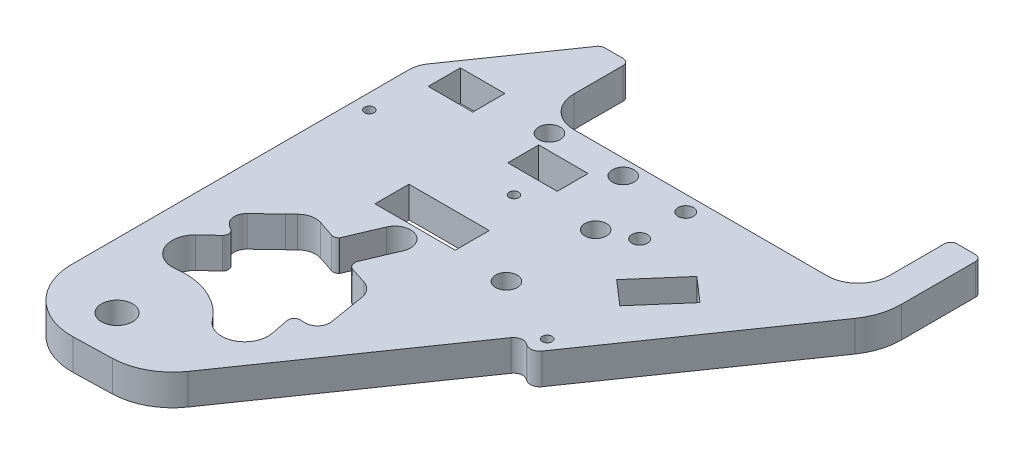
SolidWorks part; units mm, degrees
ref_plane "Płaszczyzna przednia" through (0, 0, 0) normal (0, 0, 1) x (1, 0, 0)
ref_plane "Płaszczyzna górna" through (0, 0, 0) normal (0, 1, 0) x (1, 0, 0)
ref_plane "Płaszczyzna prawa" through (0, 0, 0) normal (1, 0, 0) x (0, 0, -1)
sketch "Szkic2" plane through (0, 0, 0) normal (0, 1, 0) x (1, 0, 0)
  line L0 (-2.7059, 127.916) -> (-8.7059, 127.916)
  line L1 (-32.7793, 94.7431) -> (-10.3657, 127.0559) construction
  line L3 (103.2941, 130) -> (109.2941, 130)
  line L4 (-32.7793, 94.7431) -> (-10.3657, 127.0559)
  line L5 (-34.2059, 90.1835) -> (-34.2059, -19.1544) construction
  line L6 (-8.7059, 127.916) -> (-8.7223, 127.916)
  line L7 (111.2941, 128) -> (111.2941, 118.285)
  line L9 (-34.2059, 90.1835) -> (-34.2059, -19.1544)
  line L10 (55.0272, 21.5459) -> (-2.7136, -35.9345)
  line L11 (-0.7059, 110) -> (-0.7059, 125.916) construction
  line L12 (-13.6937, -39.1478) -> (-2.7136, -35.9345)
  line L13 (9.2941, 100) -> (91.2941, 100)
  line L14 (-0.7059, 110) -> (-0.7059, 125.916)
  line L15 (85.9359, 90.0901) -> (91.3711, 90.0901)
  line L18 (56.7941, 25.7981) -> (56.7941, 59.3339)
  line L20 (101.2941, 110) -> (101.2941, 118.285)
  line L21 (111.2941, 110.0131) -> (111.2941, 118.285)
  line L28 (101.2941, 128) -> (101.2941, 118.285)
  arc A0 (-8.7223, 127.916) -> (-10.3657, 127.0559) centre (-8.7223, 125.916) ccw construction
  arc A1 (101.2941, 110) -> (91.2941, 100) centre (91.2941, 110) cw
  arc A3 (-34.2059, -19.1544) -> (-13.6937, -39.1478) centre (-14.2059, -19.1544) ccw construction
  arc A5 (-32.7793, 94.7431) -> (-34.2059, 90.1835) centre (-26.2059, 90.1835) ccw construction
  arc A6 (91.3711, 90.0901) -> (111.2941, 110.0131) centre (91.3711, 110.0131) ccw
  arc A7 (-34.2059, -19.1544) -> (-13.6937, -39.1478) centre (-14.2059, -19.1544) ccw
  arc A8 (-8.7223, 127.916) -> (-10.3657, 127.0559) centre (-8.7223, 125.916) ccw
  arc A9 (-32.7793, 94.7431) -> (-34.2059, 90.1835) centre (-26.2059, 90.1835) ccw
  arc A10 (-0.7059, 125.916) -> (-2.7059, 127.916) centre (-2.7059, 125.916) ccw construction
  arc A11 (-0.7059, 110) -> (9.2941, 100) centre (9.2941, 110) ccw construction
  arc A12 (-0.7059, 125.916) -> (-2.7059, 127.916) centre (-2.7059, 125.916) ccw
  arc A13 (-0.7059, 110) -> (9.2941, 100) centre (9.2941, 110) ccw
  arc A15 (109.2941, 130) -> (111.2941, 128) centre (109.2941, 128) cw
  arc A16 (101.2941, 128) -> (103.2941, 130) centre (103.2941, 128) cw
  arc A20 (55.0272, 21.5459) -> (56.7941, 25.7981) centre (50.7941, 25.7981) ccw
  arc A21 (85.9359, 90.0901) -> (56.7941, 59.3339) centre (85.7027, 61.1269) ccw
  point P0 (-0.0663, -32.3728)
  point P1 (26.0174, 75.6612)
  point P7 (22.4343, 73.3976)
  point P10 (-27.8527, -17.9733)
  point P17 (-26.5261, -18.235)
  point P19 (48.8941, 59.2598)
  dimension "D8" = 2
  dimension "D2" = 10
  dimension "D3" = 10
extrude "Dodanie-wyciągnięcie1" add sketch "Szkic2" along normal blind 10 separate body
sketch "Szkic5" plane through (0, 10, 0) normal (0, 1, 0) x (1, 0, 0)
  circle A0 centre (-13.2962, -25.3039) radius 5.05
  dimension "D6" = 10.1
  dimension "D2" = 0
extrude "Wytnij-wyciągnięcie1" cut sketch "Szkic5" against normal blind 10
sketch "Szkic9" plane through (0, 10, 0) normal (0, 1, 0) x (1, 0, 0)
  line L0 (-2.1059, 47) -> (23.8941, 47) construction
  line L1 (23.8941, 47) -> (23.8941, 58) construction
  line L2 (-2.1059, 58) -> (-2.1059, 47) construction
  line L3 (23.8941, 58) -> (-2.1059, 58) construction
  line L4 (7.8941, 90) -> (7.8941, 80) construction
  line L5 (23.8941, 90) -> (7.8941, 90) construction
  line L6 (23.8941, 80) -> (23.8941, 90) construction
  line L7 (7.8941, 80) -> (23.8941, 80) construction
  line L8 (-2.1059, 47) -> (23.8941, 47)
  line L9 (23.8941, 47) -> (23.8941, 58)
  line L10 (-2.1059, 58) -> (-2.1059, 47)
  line L11 (23.8941, 58) -> (-2.1059, 58)
  line L12 (7.8941, 90) -> (7.8941, 80)
  line L13 (23.8941, 90) -> (7.8941, 90)
  line L14 (23.8941, 80) -> (23.8941, 90)
  line L15 (7.8941, 80) -> (23.8941, 80)
  circle A13 centre (17.8941, 72) radius 1.55 construction
  circle A14 centre (17.8941, 72) radius 1.55
extrude "Wytnij-wyciągnięcie3" cut sketch "Szkic9" against normal through all
sketch "Szkic12" plane through (0, 10, 0) normal (0, 1, 0) x (1, 0, 0)
  circle A0 centre (40.8941, 46.55) radius 1.55 construction
  circle A1 centre (30.2605, 95) radius 1.55 construction
  circle A2 centre (6.3605, 95) radius 1.55 construction
  circle A3 centre (40.8941, 46.55) radius 1.55
  circle A4 centre (30.2605, 95) radius 1.55
  circle A5 centre (6.3605, 95) radius 1.55
  circle A6 centre (40.8941, 75.45) radius 1.55 construction
  circle A7 centre (40.8941, 75.45) radius 1.55
  circle A8 centre (40.8941, 46.55) radius 3.5
  circle A9 centre (30.2605, 95) radius 3.5
  circle A10 centre (6.3605, 95) radius 3.5
  circle A11 centre (40.8941, 75.45) radius 3.5
  dimension "D1" = 7
  dimension "D2" = 7
  dimension "D3" = 7
  dimension "D4" = 7
sketch "Szkic13" plane through (0, 10, 0) normal (0, 1, 0) x (1, 0, 0)
  circle A0 centre (40.8941, 75.45) radius 3.5 construction
  circle A1 centre (40.8941, 46.55) radius 3.5 construction
  circle A2 centre (30.2605, 95) radius 3.5 construction
  circle A3 centre (6.3605, 95) radius 3.5 construction
  circle A4 centre (40.8941, 75.45) radius 3.5
  circle A5 centre (40.8941, 46.55) radius 3.5
  circle A6 centre (30.2605, 95) radius 3.5
  circle A7 centre (6.3605, 95) radius 3.5
extrude "Wytnij-wyciągnięcie5" cut sketch "Szkic13" against normal through all
sketch "Szkic16" plane through (0, 10, 0) normal (0, 1, 0) x (1, 0, 0)
  line L4 (78.2039, 71.9086) -> (70.359, 78.7363)
  line L5 (70.359, 78.7363) -> (58.2793, 64.8568)
  line L6 (58.2793, 64.8568) -> (66.1242, 58.0291)
  line L7 (66.1242, 58.0291) -> (78.2039, 71.9086)
  line L12 (70.3785, 78.4541) -> (58.5614, 64.8763)
  line L13 (58.5614, 64.8763) -> (66.1047, 58.3113)
  line L14 (66.1047, 58.3113) -> (77.9217, 71.8891)
  line L15 (77.9217, 71.8891) -> (70.3785, 78.4541)
  line L16 (70.3785, 78.4541) -> (58.5614, 64.8763)
  line L17 (58.5614, 64.8763) -> (66.1047, 58.3113)
  line L18 (66.1047, 58.3113) -> (77.9217, 71.8891)
  line L19 (77.9217, 71.8891) -> (70.3785, 78.4541)
  dimension "D1" = 0
  dimension "D2" = 0.2
sketch "Szkic18" plane through (0, 10, 0) normal (0, 1, 0) x (1, 0, 0)
  line L0 (-26.2059, 88.7461) -> (-26.2059, 98.7461) construction
  line L1 (-12.2059, 88.7461) -> (-12.2059, 98.7461) construction
  line L3 (-14.2059, 98.7461) -> (-24.2059, 98.7461) construction
  line L4 (-12.0059, 98.9461) -> (-26.4059, 98.9461)
  line L5 (-26.4059, 98.9461) -> (-26.4059, 88.5461)
  line L6 (-26.4059, 88.5461) -> (-12.0059, 88.5461)
  line L7 (-12.0059, 88.5461) -> (-12.0059, 98.9461)
  line L12 (-14.2059, 88.7461) -> (-24.2059, 88.7461) construction
  line L15 (-26.2059, 98.7461) -> (-26.2059, 88.7461)
  line L16 (-12.2059, 98.7461) -> (-26.2059, 98.7461)
  line L18 (-26.2059, 88.7461) -> (-12.2059, 88.7461)
  line L19 (-12.2059, 88.7461) -> (-12.2059, 98.7461)
  line L20 (-26.2059, 98.7461) -> (-26.2059, 88.7461) construction
  line L21 (-12.2059, 88.7461) -> (-12.2059, 98.7461) construction
  dimension "D3" = 0
  dimension "D1" = 0
  dimension "D4" = 0
  dimension "D5" = 0
  dimension "D2" = 0.2
sketch "Szkic19" plane through (0, 10, 0) normal (0, 1, 0) x (1, 0, 0)
  line L4 (-26.4059, 88.5461) -> (-12.0059, 88.5461) construction
  line L5 (-12.0059, 88.5461) -> (-12.0059, 98.9461) construction
  line L6 (-12.0059, 98.9461) -> (-26.4059, 98.9461) construction
  line L7 (-26.4059, 98.9461) -> (-26.4059, 88.5461) construction
  line L8 (-26.4059, 88.5461) -> (-12.0059, 88.5461)
  line L9 (-12.0059, 88.5461) -> (-12.0059, 98.9461)
  line L10 (-12.0059, 98.9461) -> (-26.4059, 98.9461)
  line L11 (-26.4059, 98.9461) -> (-26.4059, 88.5461)
extrude "Wytnij-wyciągnięcie7" cut sketch "Szkic19" against normal through all
sketch "Szkic20" plane through (0, 0, 0) normal (0, -1, 0) x (1, 0, 0)
  circle A0 centre (-29.3372, -72.3879) radius 1.55 construction
  circle A1 centre (-29.3372, -72.3879) radius 1.55
extrude "Wytnij-wyciągnięcie8" cut sketch "Szkic20" against normal blind 10
sketch "Szkic23" plane through (0, 10, 0) normal (0, 1, 0) x (1, 0, 0)
  line L0 (15.6287, 38.3507) -> (8.5974, 21.8895)
  line L1 (8.5974, 21.8895) -> (-0.7827, 25.8961)
  line L2 (-0.7827, 25.8961) -> (6.2486, 42.3573)
  line L4 (-2.7136, -35.9345) -> (55.0272, 21.5459) construction
  circle A0 centre (-13.2962, -25.3039) radius 5.05 construction
  arc A1 (15.6287, 38.3507) -> (6.2486, 42.3573) centre (10.9387, 40.354) ccw
  dimension "D8" = 10.2
  dimension "D1" = 10.2
  dimension "D2" = 17.9
  dimension "D3" = 22
  dimension "D4" = 33
  dimension "D5" = 52
  dimension "D6" = 5.1
extrude "Wytnij-wyciągnięcie10" cut sketch "Szkic23" against normal blind 10
ref_plane "Płaszczyzna1" through (-7.7499, 0, -13.8978) normal (-0.5026, 0, 0.8645) x (0.8645, 0, 0.5026)
sketch "Szkic25" plane through (0, 10, 0) normal (0, 1, 0) x (1, 0, 0)
  line L0 (1.6794, 31.6602) -> (3.4697, 35.8516)
  line L1 (-22.4924, 9.2261) -> (1.6794, 31.6602)
  line L2 (3.7047, 36.1096) -> (3.4697, 35.8516)
  line L3 (13.392, 33.1142) -> (13.4108, 33.9645)
  line L4 (11.0595, 27.6535) -> (12.0518, 29.9766)
  line L5 (8.5974, 21.8895) -> (15.6287, 38.3507) construction
  line L6 (12.0518, 29.9766) -> (13.392, 33.1142)
  line L8 (6.2486, 42.3573) -> (-0.7827, 25.8961) construction
  line L13 (8.5974, 21.8895) -> (15.6287, 38.3507) construction
  line L16 (11.0595, 27.6535) -> (17.59, -6.1675)
  arc A0 (4.0447, -11.7489) -> (17.59, -6.1675) centre (10.2038, -7.4693) ccw
  arc A1 (-15.8745, -3.4454) -> (4.0447, -11.7489) centre (-13.2962, -25.3039) cw
  arc A2 (-22.4924, 9.2261) -> (-15.8745, -3.4454) centre (-17.1701, 3.9419) ccw
  arc A12 (13.4108, 33.9645) -> (3.7047, 36.1096) centre (8.44, 34.5043) ccw
extrude "Wytnij-wyciągnięcie11" cut sketch "Szkic25" against normal blind 10
sketch "Szkic27" plane through (0, 0, 0) normal (0, -1, 0) x (1, 0, 0)
  line L0 (111.2941, -110.0131) -> (91.3711, -90.0901)
  line L1 (7.8311, 38.5964) -> (-13.6937, 39.1478)
  line L2 (-13.6937, 39.1478) -> (-2.7136, 35.9345)
  line L4 (-2.7136, 35.9345) -> (55.0272, -21.5459) construction
  line L5 (56.7941, -25.7981) -> (56.7941, -59.3339) construction
  line L6 (85.9359, -90.0901) -> (91.3711, -90.0901) construction
  line L7 (-2.7136, 35.9345) -> (55.0272, -21.5459)
  line L8 (56.7941, -25.7981) -> (56.7941, -59.3339)
  line L9 (85.9359, -90.0901) -> (91.3711, -90.0901)
  line L14 (56.7941, -25.7981) -> (55.0272, -21.5459)
  line L16 (111.2941, -110.0131) -> (111.2941, -103.9866)
  line L17 (89.1661, -65.8281) -> (107.7277, -92.5876)
  line L18 (62.7753, -27.7816) -> (22.6535, 30.0604)
  line L19 (62.7753, -27.7816) -> (89.1661, -65.8281)
  arc A5 (56.7941, -59.3339) -> (85.9359, -90.0901) centre (85.7027, -61.1269) ccw construction
  arc A6 (111.2941, -103.9866) -> (107.7277, -92.5876) centre (91.2941, -103.9866) ccw
  arc A8 (22.6535, 30.0604) -> (7.8311, 38.5964) centre (6.22, 18.6614) ccw
  arc A9 (56.7941, -59.3339) -> (85.9359, -90.0901) centre (85.7027, -61.1269) ccw
  point P0 (56.3348, -23.4958)
  point P12 (26.6533, 28.3495)
extrude "Dodanie-wyciągnięcie4" add sketch "Szkic27" against normal blind 10
sketch "Szkic22" plane through (0, 0, 0) normal (0, -1, 0) x (1, 0, 0)
  circle A0 centre (63.6687, -36.9649) radius 1.55 construction
  circle A1 centre (63.6687, -36.9649) radius 1.55
extrude "Wytnij-wyciągnięcie9" cut sketch "Szkic22" against normal blind 10
sketch "Szkic17" plane through (0, 10, 0) normal (0, 1, 0) x (1, 0, 0)
  line L4 (66.1242, 58.0291) -> (78.2039, 71.9086) construction
  line L5 (78.2039, 71.9086) -> (70.359, 78.7363) construction
  line L6 (70.359, 78.7363) -> (58.2793, 64.8568) construction
  line L7 (58.2793, 64.8568) -> (66.1242, 58.0291) construction
  line L8 (66.1242, 58.0291) -> (78.2039, 71.9086)
  line L9 (78.2039, 71.9086) -> (70.359, 78.7363)
  line L10 (70.359, 78.7363) -> (58.2793, 64.8568)
  line L11 (58.2793, 64.8568) -> (66.1242, 58.0291)
extrude "Wytnij-wyciągnięcie6" cut sketch "Szkic17" against normal through all
sketch "Szkic28" plane through (0, 10, 0) normal (0, 1, 0) x (1, 0, 0)
  line L0 (11.2675, 26.5764) -> (10.0667, 23.2711)
  line L1 (-0.359, 31.1939) -> (-5.6555, 32.9585)
  line L3 (23.0564, 12.1189) -> (22.0009, 18.6663)
  line L4 (23.0564, 12.1189) -> (23.9404, 6.9416)
  line L5 (17.59, -6.1675) -> (11.0595, 27.6535) construction
  line L6 (1.6794, 31.6602) -> (-22.4924, 9.2261) construction
  line L8 (10.0667, 23.2711) -> (13.6501, 4.7132)
  line L9 (0.6501, 28.2492) -> (-13.2033, 15.3916)
  line L10 (-18.8782, 12.5804) -> (-17.4605, 11.4471)
  line L11 (-11.6995, 31.583) -> (-13.7216, 29.6197)
  line L12 (12.6205, 25.0511) -> (17.9365, 23.3463)
  line L13 (-18.0121, 13.3752) -> (-18.8782, 12.5804)
  line L14 (1.6337, 31.6255) -> (0.6501, 28.2492)
  line L15 (-17.4605, 11.4471) -> (-13.2033, 15.3916)
  line L16 (-13.7216, 29.6197) -> (-20.0757, 23.5963)
  line L17 (-19.8828, 17.618) -> (-19.9423, 17.6696)
  line L18 (16.4018, -0.0141) -> (14.4432, -0.1511)
  line L19 (14.4432, -0.1511) -> (13.6501, 4.7132)
  line L20 (20.2493, 2.3027) -> (20.1707, 2.2976)
  arc A0 (22.0009, 18.6663) -> (17.9365, 23.3463) centre (16.112, 17.657) ccw
  arc A4 (-0.359, 31.1939) -> (1.6337, 31.6255) centre (0.2732, 33.0914) ccw
  arc A6 (12.6205, 25.0511) -> (11.2675, 26.5764) centre (13.2312, 26.9556) cw
  arc A8 (-20.0757, 23.5963) -> (-19.9423, 17.6696) centre (-17.3238, 20.6933) ccw
  arc A9 (-19.8828, 17.618) -> (-18.4206, 16.6122) centre (-14.6457, 23.6655) ccw
  arc A10 (-11.6995, 31.583) -> (-5.6555, 32.9585) centre (-7.544, 27.2901) cw
  arc A13 (-18.0121, 13.3752) -> (-18.4206, 16.6122) centre (-19.3643, 14.8488) ccw
  arc A15 (16.4018, -0.0141) -> (18.6241, 2.3483) centre (18.3655, 0.3651) cw
  arc A18 (20.2493, 2.3027) -> (23.9404, 6.9416) centre (19.9931, 6.2945) ccw
  arc A20 (18.6241, 2.3483) -> (20.1707, 2.2976) centre (19.6583, 10.2812) ccw
  point P1 (10.3053, -7.0275)
  point P6 (16.8059, 5.0026)
  point P7 (2.3201, 4.0728)
  point P8 (15.4106, 5.1193)
  point P10 (15.7451, 23.6204)
  point P45 (-13.5211, 14.5764)
  dimension "D3" = 2
  dimension "D23" = 2
  dimension "D21" = 5.9747
  dimension "D4" = 2
  dimension "D5" = 2
  dimension "D2" = 1.8
  dimension "D9" = 7.7413
  dimension "D10" = 2.8449
  dimension "D11" = 1.8056
  dimension "D12" = 10.8447
  dimension "D22" = 5.2965
  dimension "D24" = 3.5167
  dimension "D25" = 1.0091
  dimension "D26" = 6.1985
extrude "Wytnij-wyciągnięcie12" cut sketch "Szkic28" against normal blind 10
sketch "Szkic30" plane through (0, 0, 0) normal (0, -1, 0) x (1, 0, 0)
  circle A0 centre (50.5658, -80.0013) radius 2.5 construction
  circle A1 centre (50.4845, -95.0011) radius 2.5 construction
  circle A2 centre (50.5658, -80.0013) radius 2.5
  circle A3 centre (50.4845, -95.0011) radius 2.5
extrude "Wytnij-wyciągnięcie13" cut sketch "Szkic30" against normal blind 10
sketch "Szkic31" plane through (0, 0, 0) normal (0, -1, 0) x (1, 0, 0)
  line L0 (14.6211, 30.2359) -> (57.4657, -31.5314) construction
  line L1 (61.6406, -32.2866) -> (62.0515, -32.0016) construction
  line L2 (14.6211, 30.2359) -> (57.4657, -31.5314)
  line L3 (61.6406, -32.2866) -> (62.0515, -32.0016)
  line L4 (107.7277, -92.5876) -> (22.6535, 30.0604) construction
  line L5 (7.8311, 38.5964) -> (-13.6937, 39.1478) construction
  line L6 (66.2263, -32.7568) -> (22.6535, 30.0604)
  line L7 (7.8311, 38.5964) -> (-1.3002, 38.8303)
  arc A0 (14.6211, 30.2359) -> (-1.3002, 38.8303) centre (-1.8124, 18.8369) ccw construction
  arc A1 (57.4657, -31.5314) -> (61.6406, -32.2866) centre (59.9308, -29.8215) ccw construction
  arc A2 (66.2263, -32.7568) -> (62.0515, -32.0016) centre (63.7613, -34.4666) ccw construction
  arc A3 (14.6211, 30.2359) -> (-1.3002, 38.8303) centre (-1.8124, 18.8369) ccw
  arc A4 (57.4657, -31.5314) -> (61.6406, -32.2866) centre (59.9308, -29.8215) ccw
  arc A5 (66.2263, -32.7568) -> (62.0515, -32.0016) centre (63.7613, -34.4666) ccw
  arc A6 (22.6535, 30.0604) -> (7.8311, 38.5964) centre (6.22, 18.6614) ccw construction
  arc A7 (22.6535, 30.0604) -> (7.8311, 38.5964) centre (6.22, 18.6614) ccw
extrude "Wytnij-wyciągnięcie14" cut sketch "Szkic31" against normal blind 10
